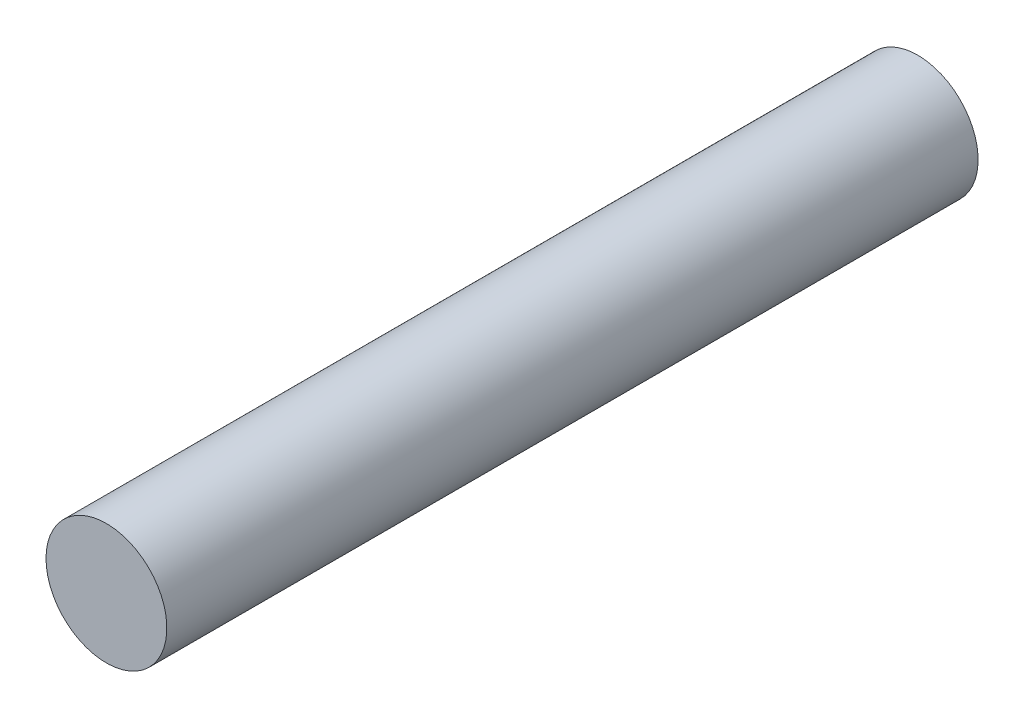
SolidWorks part; units mm, degrees
ref_plane "Alzado" through (0, 0, 0) normal (0, 0, 1) x (1, 0, 0)
ref_plane "Planta" through (0, 0, 0) normal (0, 1, 0) x (1, 0, 0)
ref_plane "Vista lateral" through (0, 0, 0) normal (1, 0, 0) x (0, 0, -1)
sketch "Croquis1" plane through (0, 0, 0) normal (0, 0, 1) x (1, 0, 0)
  circle A0 centre (0, 0) radius 4
  dimension "D1" = 8
extrude "Saliente-Extruir1" add sketch "Croquis1" along normal blind 53.7
